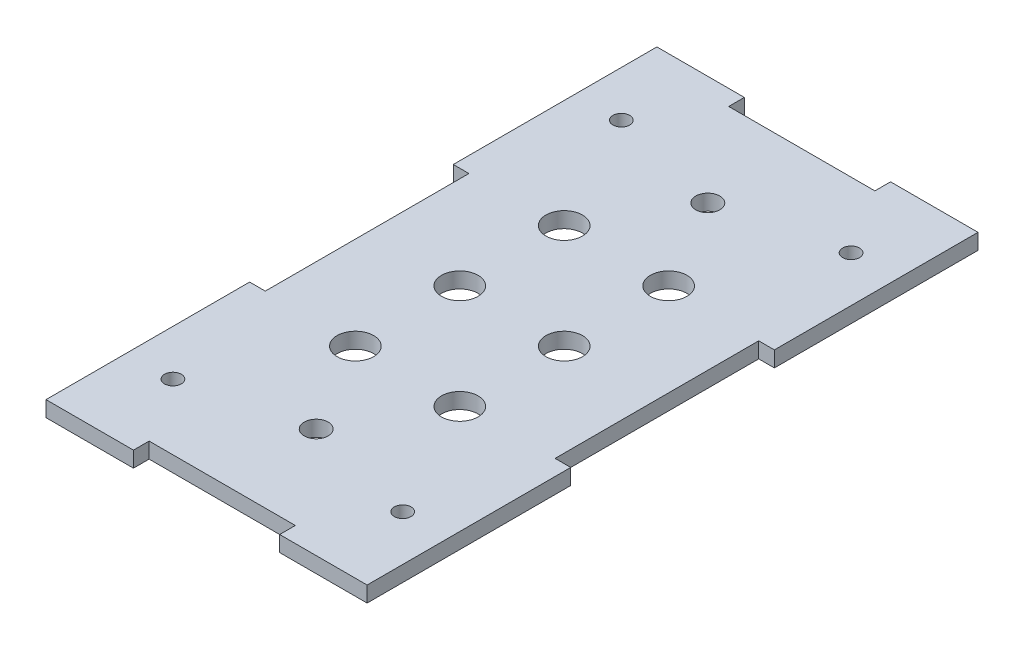
SolidWorks part; units mm, degrees
ref_plane "Front Plane" through (0, 0, 0) normal (0, 0, 1) x (1, 0, 0)
ref_plane "Top Plane" through (0, 0, 0) normal (0, 1, 0) x (1, 0, 0)
ref_plane "Right Plane" through (0, 0, 0) normal (1, 0, 0) x (0, 0, -1)
sketch "Sketch1" plane through (0, 0, 0) normal (0, 1, 0) x (1, 0, 0)
  line L0 (-30.75, 58.5) -> (-30.75, 19.5)
  line L1 (-30.75, -58.5) -> (30.75, -58.5) construction
  line L2 (-30.75, -58.5) -> (-30.75, 58.5) construction
  line L3 (-30.75, 58.5) -> (30.75, 58.5) construction
  line L4 (30.75, -58.5) -> (30.75, 58.5) construction
  line L5 (-30.75, -58.5) -> (30.75, 58.5) construction
  line L6 (-30.75, 58.5) -> (30.75, -58.5) construction
  line L7 (-27.75, -55.5) -> (27.75, -55.5) construction
  line L8 (-27.75, -55.5) -> (-27.75, 55.5) construction
  line L9 (-27.75, 55.5) -> (27.75, 55.5) construction
  line L10 (27.75, -55.5) -> (27.75, 55.5) construction
  line L11 (-27.75, -55.5) -> (27.75, 55.5) construction
  line L12 (-27.75, 55.5) -> (27.75, -55.5) construction
  line L13 (-30.75, 19.5) -> (-27.75, 19.5)
  line L14 (-27.75, 19.5) -> (-27.75, -19.5)
  line L15 (-27.75, -19.5) -> (-30.75, -19.5)
  line L16 (-30.75, -19.5) -> (-30.75, -58.5)
  line L17 (-30.75, -58.5) -> (-14, -58.5)
  line L18 (-14, -58.5) -> (-14, -55.5)
  line L19 (-14, -55.5) -> (14, -55.5)
  line L20 (14, -55.5) -> (14, -58.5)
  line L21 (14, -58.5) -> (30.75, -58.5)
  line L22 (30.75, -58.5) -> (30.75, -19.5)
  line L23 (30.75, -19.5) -> (27.75, -19.5)
  line L24 (27.75, -19.5) -> (27.75, 19.5)
  line L25 (27.75, 19.5) -> (30.75, 19.5)
  line L26 (30.75, 19.5) -> (30.75, 58.5)
  line L27 (30.75, 58.5) -> (14, 58.5)
  line L28 (14, 58.5) -> (14, 55.5)
  line L29 (14, 55.5) -> (-14, 55.5)
  line L30 (-14, 55.5) -> (-14, 58.5)
  line L31 (-14, 58.5) -> (-30.75, 58.5)
  line L32 (0, -37.5) -> (0, 37.5) construction
  line L33 (-22, 42.94) -> (22, 42.94) construction
  line L35 (-10, 0) -> (10, 0) construction
  circle A2 centre (-22, -42.94) radius 1.6092
  circle A3 centre (22, -42.94) radius 1.6092
  circle A4 centre (22, 42.94) radius 1.6092
  circle A5 centre (-22, 42.94) radius 1.6092
  circle A6 centre (0, 37.5) radius 2.3
  circle A7 centre (0, -37.5) radius 2.3
  circle A10 centre (-10, -20) radius 3.5
  circle A11 centre (10, -20) radius 3.5
  circle A12 centre (-10, 0) radius 3.5
  circle A13 centre (10, 0) radius 3.5
  circle A14 centre (-10, 20) radius 3.5
  circle A15 centre (10, 20) radius 3.5
  point P0 (0, 0)
  point P6 (0, 0)
  point P41 (0, 0)
  point P45 (0, 0)
  dimension "D6" = 4.6
  dimension "D1" = 61.5
  dimension "D2" = 117
  dimension "D3" = 3
  dimension "D4" = 3
  dimension "D5" = 75
  dimension "D7" = 44
  dimension "D8" = 85.88
  dimension "D9" = 28
  dimension "D11" = 20
extrude "Boss-Extrude1" add sketch "Sketch1" along normal blind 3
